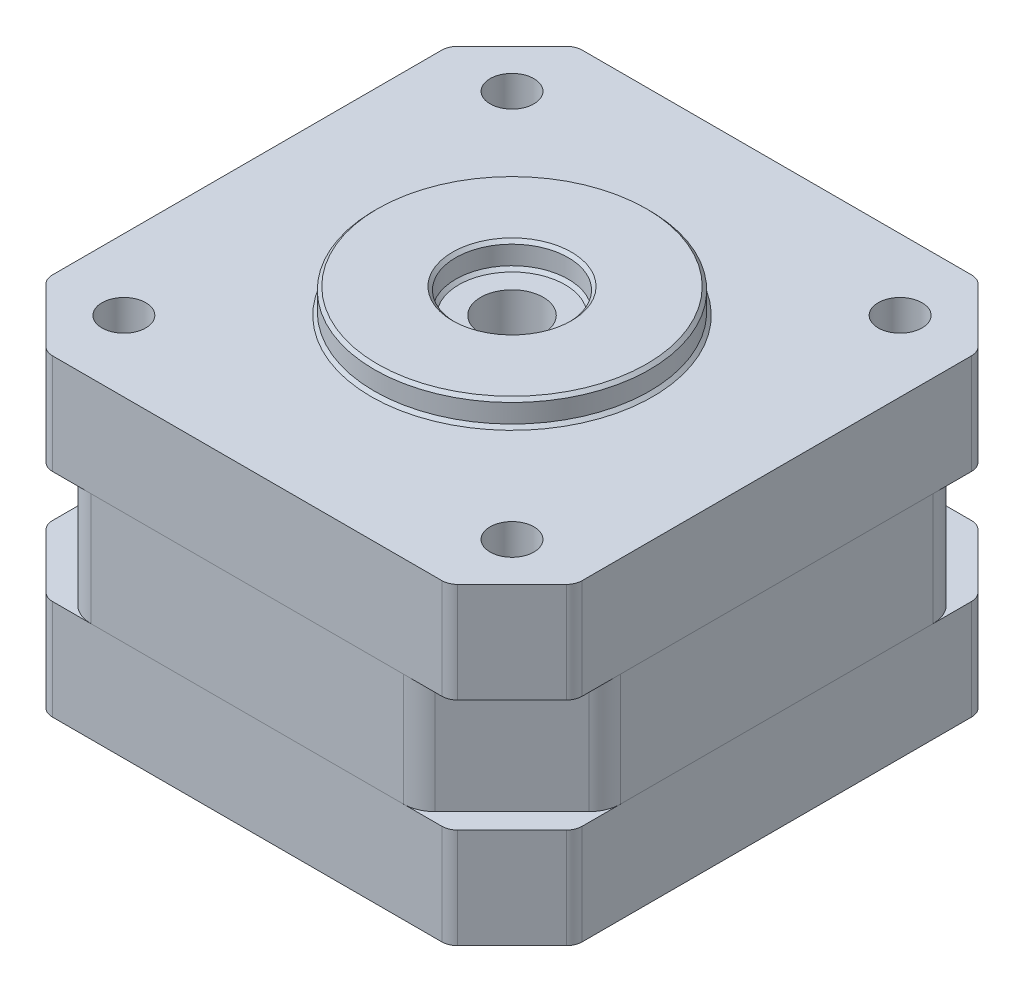
SolidWorks part; units mm, degrees
ref_plane "Front Plane" through (0, 0, 0) normal (0, 0, 1) x (1, 0, 0)
ref_plane "Top Plane" through (0, 0, 0) normal (0, 1, 0) x (1, 0, 0)
ref_plane "Right Plane" through (0, 0, 0) normal (1, 0, 0) x (0, 0, -1)
sketch "Sketch1" plane through (0, 0, 0) normal (0, 1, 0) x (1, 0, 0)
  line L1 (-21.15, 21.15) -> (21.15, 21.15)
  line L2 (-21.15, 21.15) -> (-21.15, -21.15)
  line L3 (-21.15, -21.15) -> (21.15, -21.15)
  line L4 (21.15, 21.15) -> (21.15, -21.15)
  line L5 (-21.15, 21.15) -> (21.15, -21.15) construction
  line L6 (-21.15, -21.15) -> (21.15, 21.15) construction
  point P0 (0, 0)
  dimension "D1" = 42.3
extrude "Boss-Extrude1" add sketch "Sketch1" along normal blind 8.001
chamfer "Chamfer1" distance 5.08 angle 45 4 edges at (-21.15, 4.0005, 21.15) (-21.15, 4.0005, -21.15) (21.15, 4.0005, -21.15) (21.15, 4.0005, 21.15)
sketch "Sketch2" plane through (0, 8.001, 0) normal (0, 1, 0) x (1, 0, 0)
  line L0 (16.07, 21.15) -> (-16.07, 21.15) construction
  line L1 (-21.15, -21.15) -> (21.15, -21.15)
  line L2 (-21.15, -21.15) -> (-21.15, 21.15)
  line L3 (-21.15, 21.15) -> (21.15, 21.15)
  line L4 (21.15, -21.15) -> (21.15, 21.15)
  line L5 (-21.15, -21.15) -> (21.15, 21.15) construction
  line L6 (-21.15, 21.15) -> (21.15, -21.15) construction
  line L7 (21.15, -16.07) -> (21.15, 16.07) construction
  point P0 (0, 0)
extrude "Boss-Extrude2" add sketch "Sketch2" along normal blind 8.9916 separate body
chamfer "Chamfer3" distance 7.62 angle 45 4 edges at (-21.15, 12.4968, -21.15) (-21.15, 12.4968, 21.15) (21.15, 12.4968, 21.15) (21.15, 12.4968, -21.15)
fillet "Fillet1" radius 2.54 8 edges at (-21.15, 12.4968, -13.53) (-13.53, 12.4968, -21.15) (13.53, 12.4968, -21.15) (21.15, 12.4968, -13.53) (21.15, 12.4968, 13.53) (13.53, 12.4968, 21.15) (-13.53, 12.4968, 21.15) (-21.15, 12.4968, 13.53)
fillet "Fillet2" radius 1.27 8 edges at (-21.15, 4.0005, -16.07) (-16.07, 4.0005, -21.15) (16.07, 4.0005, -21.15) (21.15, 4.0005, -16.07) (21.15, 4.0005, 16.07) (16.07, 4.0005, 21.15) (-16.07, 4.0005, 21.15) (-21.15, 4.0005, 16.07)
sketch "Sketch3" plane through (0, 16.9926, 0) normal (0, 1, 0) x (1, 0, 0)
  line L0 (21.15, -12.4779) -> (21.15, 12.4779) construction
  line L1 (-21.15, 21.15) -> (21.15, 21.15)
  line L2 (-21.15, 21.15) -> (-21.15, -21.15)
  line L3 (-21.15, -21.15) -> (21.15, -21.15)
  line L4 (21.15, 21.15) -> (21.15, -21.15)
  line L5 (-21.15, 21.15) -> (21.15, -21.15) construction
  line L6 (-21.15, -21.15) -> (21.15, 21.15) construction
  line L7 (12.4779, 21.15) -> (-12.4779, 21.15) construction
  point P0 (0, 0)
extrude "Boss-Extrude3" add sketch "Sketch3" along normal blind 8.001 separate body
chamfer "Chamfer4" distance 5.08 angle 45 4 edges at (-21.15, 20.9931, 21.15) (-21.15, 20.9931, -21.15) (21.15, 20.9931, -21.15) (21.15, 20.9931, 21.15)
fillet "Fillet3" radius 1.27 8 edges at (-21.15, 20.9931, -16.07) (-16.07, 20.9931, -21.15) (16.07, 20.9931, -21.15) (21.15, 20.9931, -16.07) (21.15, 20.9931, 16.07) (16.07, 20.9931, 21.15) (-16.07, 20.9931, 21.15) (-21.15, 20.9931, 16.07)
sketch "Sketch4" plane through (0, 24.9936, 0) normal (0, 1, 0) x (1, 0, 0)
  circle A0 centre (0, 0) radius 10.9982
  circle A1 centre (0, 0) radius 4.4958
  dimension "D1" = 21.9964
  dimension "D2" = 8.9916
extrude "Boss-Extrude4" add sketch "Sketch4" along normal blind 2
chamfer "Chamfer5" distance 0.254 angle 45 4 edges at (0, 26.9936, 10.9982) (0, 24.9936, 10.9982) (0, 24.9936, 4.4958) (0, 26.9936, 4.4958)
sketch "Sketch5" plane through (0, 24.9936, 0) normal (0, 1, 0) x (1, 0, 0)
  circle A0 centre (0, 0) radius 2.5019
  dimension "D1" = 5.0038
extrude "Cut-Extrude1" cut sketch "Sketch5" against normal blind 12.7
sketch "Sketch6" plane through (0, 24.9936, 0) normal (0, 1, 0) x (1, 0, 0)
  line L0 (21.15, -15.5439) -> (21.15, 15.5439) construction
  line L1 (-15.5439, -21.15) -> (15.5439, -21.15) construction
  circle A0 centre (15.5, -15.5) radius 1.75
  circle A1 centre (-15.5, -15.5) radius 1.75
  circle A2 centre (-15.5, 15.5) radius 1.75
  circle A3 centre (15.5, 15.5) radius 1.75
  dimension "D1" = 3.5
  dimension "D2" = 5.65
  dimension "D3" = 5.65
  dimension "D4" = 2
  dimension "D5" = 2
extrude "Cut-Extrude2" cut sketch "Sketch6" against normal through all
